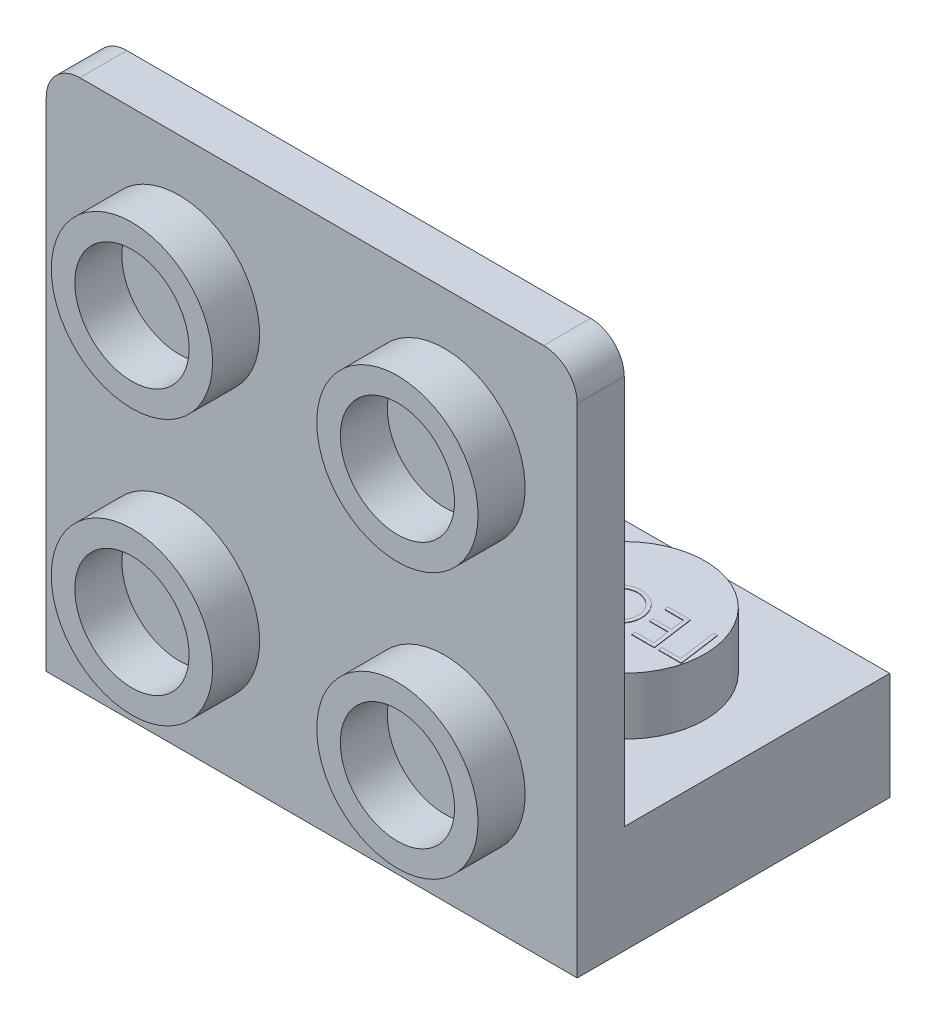
SolidWorks part; units mm, degrees
ref_plane "Front Plane" through (0, 0, 0) normal (0, 0, 1) x (1, 0, 0)
ref_plane "Top Plane" through (0, 0, 0) normal (0, 1, 0) x (1, 0, 0)
ref_plane "Right Plane" through (0, 0, 0) normal (1, 0, 0) x (0, 0, -1)
sketch "Sketch1" plane through (0, 0, 0) normal (0, 1, 0) x (1, 0, 0)
  line L0 (0, 0) -> (7.9, 0)
  line L1 (7.9, 0) -> (7.9, 7.9)
  line L2 (0, 0) -> (0, 7.9)
  line L3 (0, 7.9) -> (7.9, 7.9)
  dimension "D1" = 7.9
  dimension "D2" = 7.9
  dimension "D3" = 7.9
extrude "Boss-Extrude1" add sketch "Sketch1" along normal blind 3.2
sketch "Sketch2" plane through (0, 3.2, 0) normal (0, 1, 0) x (1, 0, 0)
  line L0 (0, 7.9) -> (7.9, 0) construction
  circle A0 centre (3.95, 3.95) radius 2.4
extrude "Boss-Extrude2" add sketch "Sketch2" along normal blind 1.7
sketch "Sketch3" plane through (0, 4.9, 0) normal (0, 1, 0) x (1, 0, 0)
  line L0 (1.625, 3.3549) -> (6.275, 3.3549) construction
  circle A0 centre (3.95, 3.95) radius 2.4 construction
  circle A1 centre (3.95, 3.95) radius 2.4 construction
  text T0 "<i>LEGO</i>" font "Century Gothic" height 1.25
extrude "Boss-Extrude4" add sketch "Sketch3" along normal blind 0.01
sketch "Sketch4" plane through (0, 0, 0) normal (0, -1, 0) x (1, 0, 0)
  line L0 (7.9, -7.9) -> (0, -7.9) construction
  line L1 (7.3, -7.3) -> (0.6204, -7.3)
  line L2 (7.3, -7.3) -> (7.3, -0.6204)
  line L3 (7.3, -0.6204) -> (0.6204, -0.6204)
  line L4 (0.6204, -7.3) -> (0.6204, -0.6204)
  line L5 (7.9, 0) -> (7.9, -7.9) construction
  dimension "D1" = 0.6
  dimension "D2" = 0.6
extrude "Cut-Extrude1" cut sketch "Sketch4" against normal blind 2.01 contours L2 L1 L4 L3
sketch "Sketch5" plane through (0, 3.2, 0) normal (0, 1, 0) x (1, 0, 0)
  line L1 (1.4581, 1.5578) -> (6.3695, 1.5578)
  line L2 (1.4581, 1.5578) -> (1.4581, 6.3652)
  line L3 (1.4581, 6.3652) -> (6.3695, 6.3652)
  line L4 (6.3695, 1.5578) -> (6.3695, 6.3652)
  circle A1 centre (6.3695, 6.3652) radius 1.0161
  circle A2 centre (6.3695, 1.5578) radius 1.0061
  circle A3 centre (1.4581, 1.5578) radius 1.0219
  circle A4 centre (1.4581, 6.3652) radius 1.0411
  circle M5 centre (3.95, 3.95) radius 2.4
extrude "Boss-Extrude5" add sketch "Sketch5" against normal blind 2.01 contours L1 A2 L4 | L2 A3 L1 | L1 A3 L2 | L4 A2 L1 M5 | L4 A1 L3 | L3 A1 L4 | L2 A4 L3 | L3 A4 L2
mirror "Mirror1" about plane through (7.9, 3.2, 0) normal (-1, 0, 0) of bodies 106
sketch "Sketch6" plane through (0, 0, 0) normal (0, 0, 1) x (1, 0, 0)
  line L1 (0, 0) -> (15.8, 0)
  line L2 (0, 0) -> (0, 15.8)
  line L3 (0, 15.8) -> (15.8, 15.8)
  line L4 (15.8, 0) -> (15.8, 15.8)
  dimension "D1" = 15.8
  dimension "D2" = 15.8
extrude "Boss-Extrude6" add sketch "Sketch6" along normal blind 1.4
sketch "Sketch7" plane through (0, 0, 1.4) normal (0, 0, 1) x (1, 0, 0)
  line L0 (7.9, 0) -> (0, 7.9) construction
  line L1 (0, 0) -> (15.8, 0) construction
  line L2 (0, 15.8) -> (0, 0) construction
  line L3 (0, 0) -> (15.8, 15.8) construction
  line L4 (15.8, 7.9) -> (0, 7.9) construction
  line L5 (15.8, 0) -> (15.8, 15.8) construction
  line L6 (7.9, 0) -> (7.9, 15.8) construction
  line L7 (15.8, 15.8) -> (0, 15.8) construction
  circle A0 centre (3.95, 3.95) radius 2.4
  circle A1 centre (3.95, 3.95) radius 1.7
  circle A2 centre (11.85, 3.95) radius 2.4
  circle A3 centre (11.85, 3.95) radius 1.7
  circle A4 centre (11.85, 11.85) radius 2.4
  circle A5 centre (11.85, 11.85) radius 1.7
  circle A6 centre (3.95, 11.85) radius 2.4
  circle A7 centre (3.95, 11.85) radius 1.7
  dimension "D1" = 4.8
  dimension "D2" = 3.4
  dimension "D3" = 2
extrude "Boss-Extrude7" add sketch "Sketch7" along normal blind 1.4
fillet "Fillet1" radius 1 2 edges at (0, 15.8, 0.7) (15.8, 15.8, 0.7)
